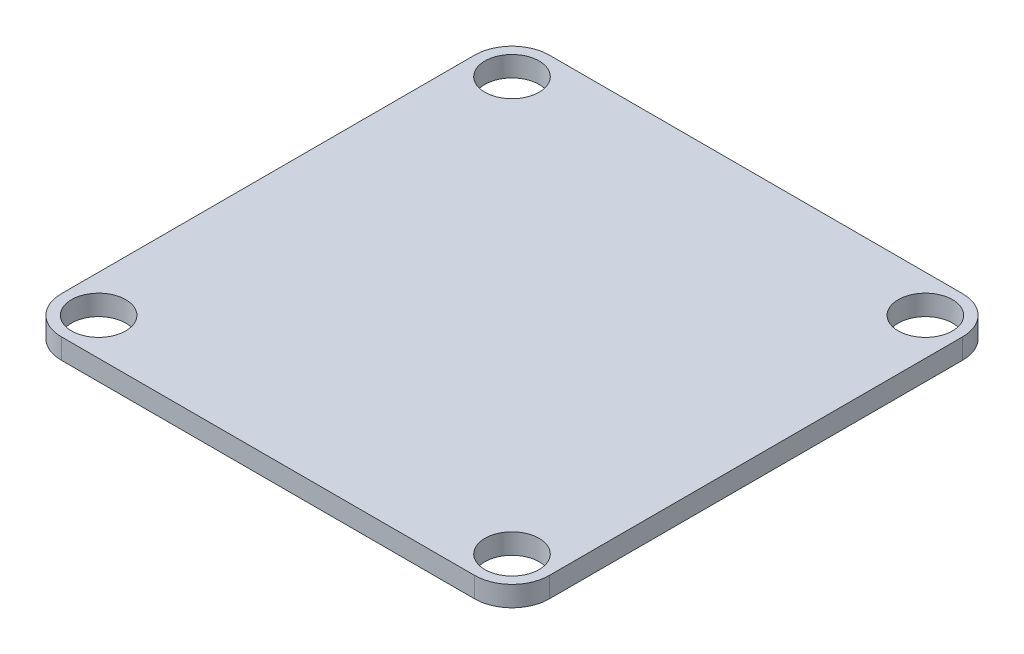
SolidWorks part; units mm, degrees
ref_plane "前视基准面" through (0, 0, 0) normal (0, 0, 1) x (1, 0, 0)
ref_plane "上视基准面" through (0, 0, 0) normal (0, 1, 0) x (1, 0, 0)
ref_plane "右视基准面" through (0, 0, 0) normal (1, 0, 0) x (0, 0, -1)
other "Configuration Table"
sketch "草图1" plane through (0, 0, 0) normal (0, 1, 0) x (1, 0, 0)
  line L0 (-18, 0) -> (18, 0) construction
  line L1 (-15.25, -18) -> (15.25, -18)
  line L2 (-18, -15.25) -> (-18, 15.25)
  line L3 (-15.25, 18) -> (15.25, 18)
  line L4 (18, -15.25) -> (18, 15.25)
  line L5 (-18, -18) -> (18, 18) construction
  line L6 (-18, 18) -> (18, -18) construction
  line L7 (0, -18) -> (0, 18) construction
  circle A0 centre (15.25, 15.25) radius 2
  circle A1 centre (15.25, -15.25) radius 2
  circle A2 centre (-15.25, -15.25) radius 2
  circle A3 centre (-15.25, 15.25) radius 2
  arc A4 (15.25, -18) -> (18, -15.25) centre (15.25, -15.25) ccw
  arc A5 (15.25, 18) -> (18, 15.25) centre (15.25, 15.25) cw
  arc A6 (-18, 15.25) -> (-15.25, 18) centre (-15.25, 15.25) cw
  arc A7 (-15.25, -18) -> (-18, -15.25) centre (-15.25, -15.25) cw
  point P0 (0, 0)
  point P9 (0, 0)
  point P12 (0, 0)
  point P23 (0, 0)
  dimension "D3" = 4
  dimension "D6" = 2.75
  dimension "D1" = 36
  dimension "D2" = 36
  dimension "D4" = 15.25
  dimension "D5" = 4
extrude "凸台-拉伸1" add sketch "草图1" along normal blind 1.5
